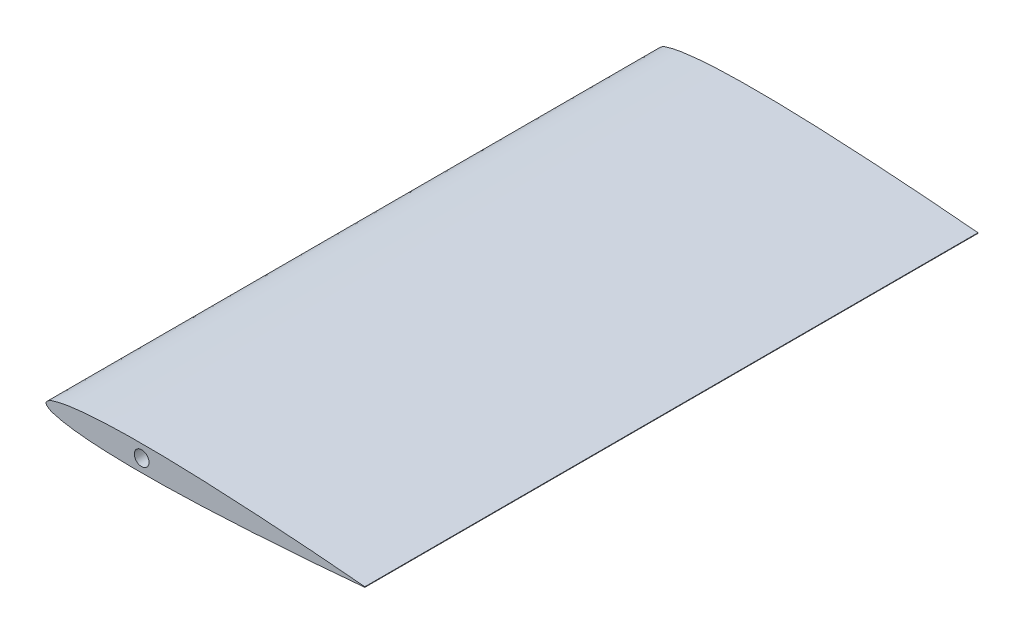
SolidWorks part; units mm, degrees
ref_plane "Piano frontale" through (0, 0, 0) normal (0, 0, 1) x (1, 0, 0)
ref_plane "Piano superiore" through (0, 0, 0) normal (0, 1, 0) x (1, 0, 0)
ref_plane "Piano destro" through (0, 0, 0) normal (1, 0, 0) x (0, 0, -1)
curve "Curva1"
  spline degree 3 poles (130, 0.1092, 0) (127.8335, 0.3078, 0) (123.5016, 0.7048, 0) (114.8362, 1.4441, 0) (104.0043, 2.2932, 0) (91.0039, 3.1952, 0) (78.004, 3.9803, 0) (65.0039, 4.6181, 0) (52.0034, 5.0743, 0) (41.167, 5.2326, 0) (32.4989, 5.1694, 0) (25.9971, 4.9995, 0) (19.4914, 4.6698, 0) (14.0754, 4.2085, 0) (9.7358, 3.6582, 0) (6.4916, 3.1252, 0) (3.7045, 2.4284, 0) (1.515, 1.7174, 0) (-0.864, 0, 0) (1.515, -1.7174, 0) (3.7045, -2.4284, 0) (6.4916, -3.1252, 0) (9.7358, -3.6582, 0) (14.0754, -4.2085, 0) (19.4914, -4.6698, 0) (25.9971, -4.9995, 0) (32.4989, -5.1694, 0) (41.167, -5.2326, 0) (52.0034, -5.0743, 0) (65.0039, -4.6181, 0) (78.004, -3.9803, 0) (91.0039, -3.1952, 0) (104.0043, -2.2932, 0) (114.8362, -1.4441, 0) (123.5016, -0.7048, 0) (127.8335, -0.3078, 0) (130, -0.1092, 0) knots 0 0 0 0 0.024876 0.049742 0.099443 0.149112 0.198751 0.248359 0.297937 0.347491 0.372267 0.397051 0.421859 0.446731 0.45922 0.47179 0.48456 0.491195 0.5 0.508805 0.51544 0.52821 0.54078 0.553269 0.578141 0.602949 0.627733 0.652509 0.702063 0.751641 0.801249 0.850888 0.900557 0.950258 0.975124 1 1 1 1
sketch "Schizzo2" plane through (0, 0, 0) normal (0, 0, 1) x (1, 0, 0)
  line L0 (130, 0.1092) -> (130, -0.1092)
  line L1 (130, 0) -> (0, 0) construction
  line L2 (38.9973, 0) -> (38.9973, 5.201) construction
  line L3 (0, 5.201) -> (130, 5.201) construction
  line L4 (0, 5.201) -> (0, -5.201) construction
  line L5 (0, -5.201) -> (130, -5.201) construction
  line L6 (130, 5.201) -> (130, -5.201) construction
  circle A0 centre (38.9973, 0) radius 3
  spline S0 degree 3 poles (880.4323, 2880.1258) (451.1085, -68.4288) (286.9568, -13.2402) (114.8362, 1.4441) (104.0043, 2.2932) (91.0039, 3.1952) (78.004, 3.9803) (65.0039, 4.6181) (52.0034, 5.0743) (41.167, 5.2326) (32.4989, 5.1694) (25.9971, 4.9995) (19.4914, 4.6698) (14.0754, 4.2085) (9.7358, 3.6582) (6.4916, 3.1252) (3.7045, 2.4284) (1.515, 1.7174) (-0.864, 0) (1.515, -1.7174) (3.7045, -2.4284) (6.4916, -3.1252) (9.7358, -3.6582) (14.0754, -4.2085) (19.4914, -4.6698) (25.9971, -4.9995) (32.4989, -5.1694) (41.167, -5.2326) (52.0034, -5.0743) (65.0039, -4.6181) (78.004, -3.9803) (91.0039, -3.1952) (104.0043, -2.2932) (114.8362, -1.4441) (286.9558, 13.2401) (451.1064, 68.4281) (880.4242, -2880.0701) knots -1.875813 -1.875813 -1.875813 -1.875813 0.024876 0.049742 0.099443 0.149112 0.198751 0.248359 0.297937 0.347491 0.372267 0.397051 0.421859 0.446731 0.45922 0.47179 0.48456 0.491195 0.5 0.508805 0.51544 0.52821 0.54078 0.553269 0.578141 0.602949 0.627733 0.652509 0.702063 0.751641 0.801249 0.850888 0.900557 0.950258 0.975124 2.875801 2.875801 2.875801 2.875801 only from (130, 0.1092) to (130, -0.1092) construction
  spline S1 degree 3 poles (130, 0.1092) (127.8335, 0.3078) (123.5016, 0.7048) (114.8362, 1.4441) (104.0043, 2.2932) (91.0039, 3.1952) (78.004, 3.9803) (65.0039, 4.6181) (52.0034, 5.0743) (41.167, 5.2326) (32.4989, 5.1694) (25.9971, 4.9995) (19.4914, 4.6698) (14.0754, 4.2085) (9.7358, 3.6582) (6.4916, 3.1252) (3.7045, 2.4284) (1.515, 1.7174) (-0.864, 0) (1.515, -1.7174) (3.7045, -2.4284) (6.4916, -3.1252) (9.7358, -3.6582) (14.0754, -4.2085) (19.4914, -4.6698) (25.9971, -4.9995) (32.4989, -5.1694) (41.167, -5.2326) (52.0034, -5.0743) (65.0039, -4.6181) (78.004, -3.9803) (91.0039, -3.1952) (104.0043, -2.2932) (114.8362, -1.4441) (123.5016, -0.7048) (127.8335, -0.3078) (130, -0.1092) knots 0 0 0 0 0.024876 0.049742 0.099443 0.149112 0.198751 0.248359 0.297937 0.347491 0.372267 0.397051 0.421859 0.446731 0.45922 0.47179 0.48456 0.491195 0.5 0.508805 0.51544 0.52821 0.54078 0.553269 0.578141 0.602949 0.627733 0.652509 0.702063 0.751641 0.801249 0.850888 0.900557 0.950258 0.975124 1 1 1 1
  point P12 (37.283, 5.1976)
  dimension "D1" = 6
extrude "Estrusione-Estrusione1" add sketch "Schizzo2" along normal blind 250
